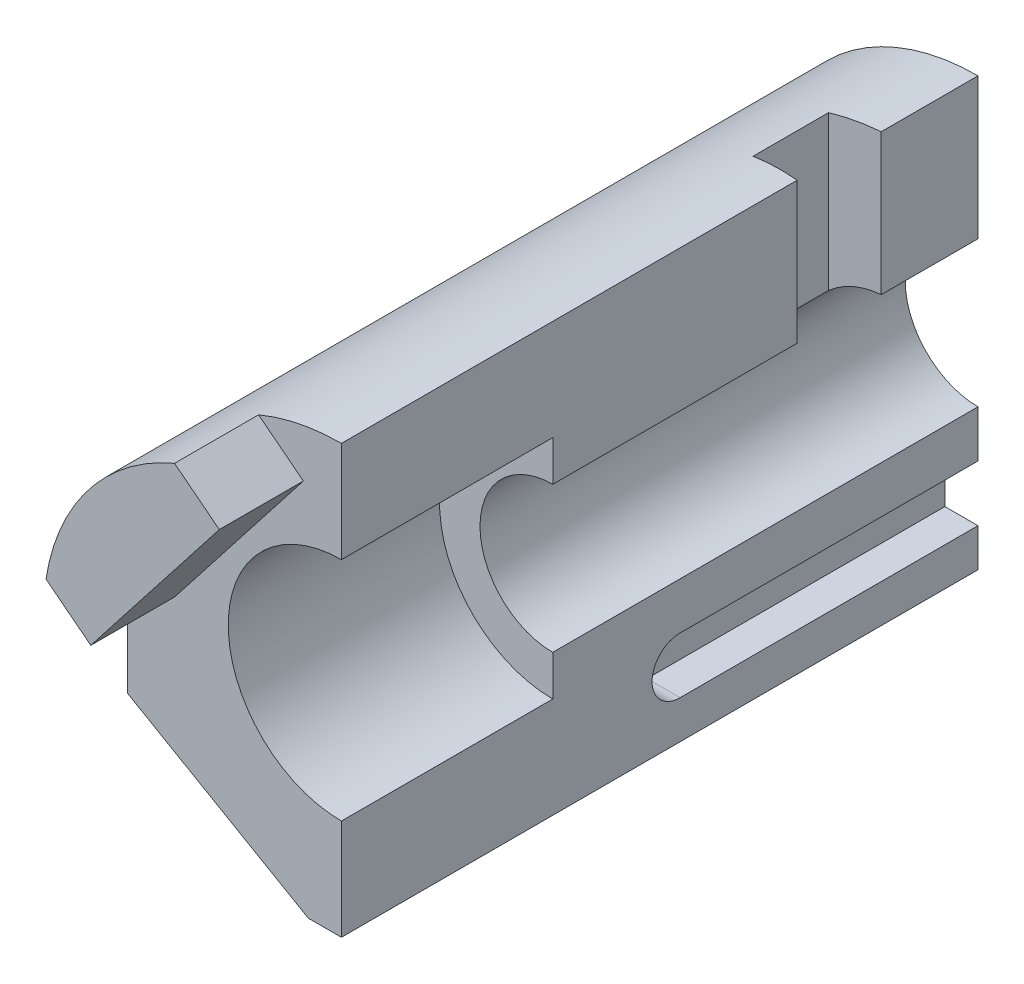
SolidWorks part; units mm, degrees
material "1060 Alloy"
ref_plane "Front Plane" through (0, 0, 0) normal (0, 0, 1) x (1, 0, 0)
ref_plane "Top Plane" through (0, 0, 0) normal (0, 1, 0) x (1, 0, 0)
ref_plane "Right Plane" through (0, 0, 0) normal (1, 0, 0) x (0, 0, -1)
sketch "Sketch1" plane through (0, 0, 0) normal (0, 0, 1) x (1, 0, 0)
  line L2 (-84, 0) -> (-84, -43.0081)
  line L3 (-84, -43.0081) -> (-13, -84)
  line L4 (-13, -84) -> (0, -84)
  line L5 (0, -84) -> (0, -44.45)
  line L6 (0, 0) -> (0, 117.9617) construction
  line L7 (0, 117.9617) -> (0, 0) construction
  line L8 (0, 0) -> (0, -132.6275) construction
  line L9 (0, 44.45) -> (0, 84)
  arc A2 (0, 84) -> (-84, 0) centre (0, 0) ccw
  arc A3 (0, 44.45) -> (0, -44.45) centre (0, 0) ccw
  point P13 (-13, -116.9258)
  dimension "D1" = 84
  dimension "D2" = 13
  dimension "D3" = 88.9
  dimension "D4" = 30
  dimension "D5" = 84
extrude "Boss-Extrude1" add sketch "Sketch1" against normal blind 250
sketch "Sketch2" plane through (0, 0, -250) normal (0, 0, -1) x (-1, 0, 0)
  line L0 (0, 28.575) -> (0, 44.45)
  line L1 (0, -28.575) -> (0, -44.45)
  arc A0 (0, -44.45) -> (0, 44.45) centre (0, 0) ccw construction
  arc A1 (0, 28.575) -> (0, -28.575) centre (0, 0) cw
  arc A3 (0, -44.45) -> (0, 44.45) centre (0, 0) ccw
  dimension "D2" = 28.575
extrude "Boss-Extrude2" add sketch "Sketch2" against normal blind 167
ref_plane "Plane1" through (0, 84, 0) normal (0, 1, 0) x (1, 0, 0)
sketch "Sketch3" plane through (0, 84, 0) normal (0, 1, 0) x (1, 0, 0)
  line L0 (0, 250) -> (0, 0) construction
  line L2 (0, 179) -> (0, 212)
  line L6 (0, 179) -> (-19, 180.6623)
  line L7 (-19, 180.6623) -> (-19, 210.3377)
  line L8 (-19, 210.3377) -> (0, 212)
  line L9 (0, 250) -> (-84, 250) construction
  dimension "D1" = 38
  dimension "D2" = 33
  dimension "D3" = 19
  dimension "D4" = 95
  dimension "D5" = 95
extrude "Cut-Extrude1" cut sketch "Sketch3" against normal up to surface (55.425 mm away)
sketch "Sketch4" plane through (0, 0, 0) normal (0, 0, 1) x (1, 0, 0)
  line L0 (-83.0146, 12.8284) -> (-65.4307, -0.9097)
  line L1 (-65.4307, -0.9097) -> (-14.9464, 63.7072)
  line L2 (-14.9464, 63.7072) -> (-32.5304, 77.4453)
  line L3 (0, 0) -> (-84.2073, 65.79) construction
  line L4 (0, 0) -> (-127.7617, 0) construction
  arc A0 (0, 84) -> (-84, 0) centre (0, 0) ccw construction
  arc A1 (-32.5304, 77.4453) -> (-83.0146, 12.8284) centre (0, 0) ccw
  dimension "D1" = 38
  dimension "D2" = 51
  dimension "D3" = 41
  dimension "D4" = 41
extrude "Boss-Extrude3" add sketch "Sketch4" along normal blind 33
sketch "Sketch5" plane through (0, 0, 0) normal (1, 0, 0) x (0, 0, -1)
  line L0 (250, -58) -> (133, -58) construction
  line L1 (250, -84) -> (250, -28.575) construction
  line L2 (250, -69) -> (133, -69)
  line L3 (250, -47) -> (133, -47)
  line L4 (250, -84) -> (0, -84) construction
  arc A0 (250, -69) -> (250, -47) centre (250, -58) ccw
  arc A1 (133, -47) -> (133, -69) centre (133, -58) ccw
  point P4 (191.5, -58)
  dimension "D1" = 11
  dimension "D2" = 26
  dimension "D3" = 117
extrude "Cut-Extrude2" cut sketch "Sketch5" against normal blind 13
